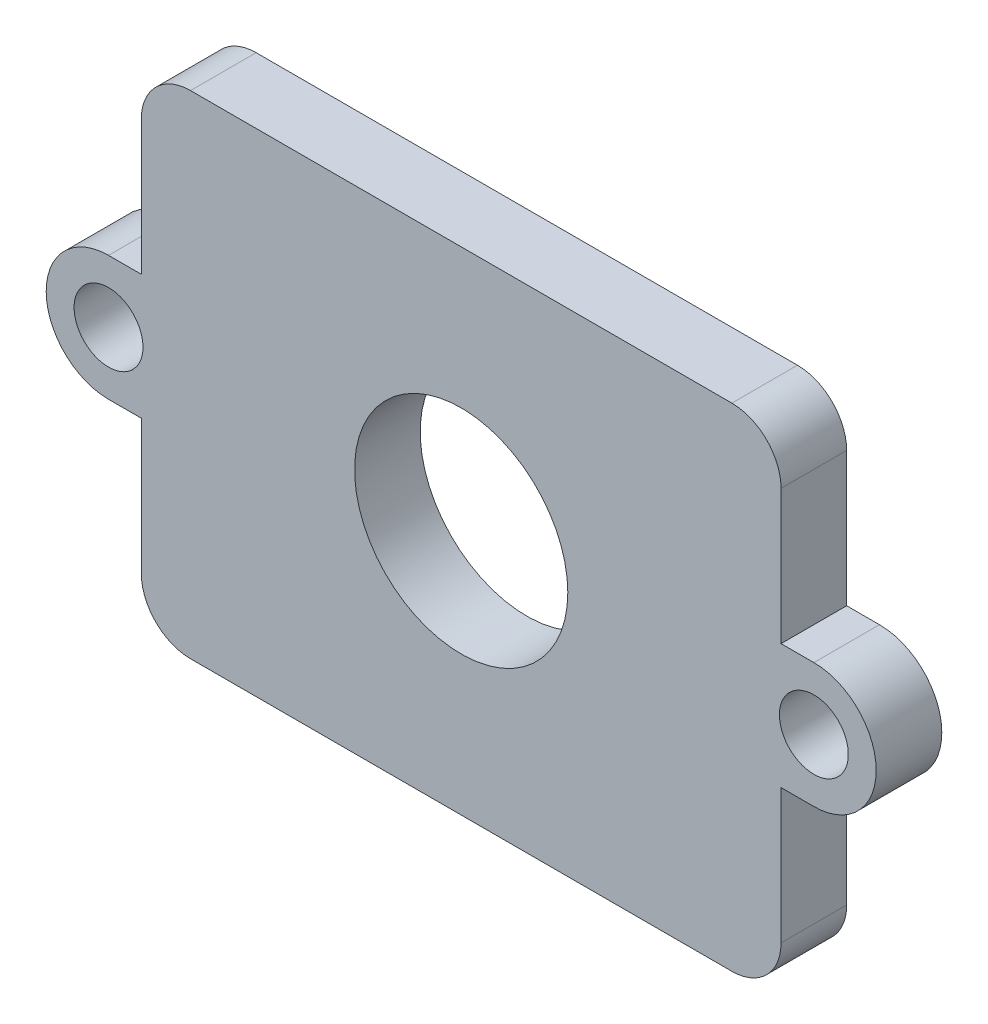
SolidWorks part; units mm, degrees
ref_plane "Front Plane" through (0, 0, 0) normal (0, 0, 1) x (1, 0, 0)
ref_plane "Top Plane" through (0, 0, 0) normal (0, 1, 0) x (1, 0, 0)
ref_plane "Right Plane" through (0, 0, 0) normal (1, 0, 0) x (0, 0, -1)
sketch "Sketch1" plane through (0, 0, 0) normal (0, 0, 1) x (1, 0, 0)
  line L0 (19.5, 3.8) -> (21.5, 3.8)
  line L1 (-19.5, 15) -> (19.5, 15)
  line L3 (-19.5, -15) -> (19.5, -15)
  line L4 (19.5, 15) -> (19.5, 3.8)
  line L5 (-19.5, 15) -> (19.5, -15) construction
  line L6 (-19.5, -15) -> (19.5, 15) construction
  line L7 (21.5, 3.8) -> (21.5, -3.8)
  line L8 (21.5, -3.8) -> (19.5, -3.8)
  line L9 (0, 15) -> (0, -15) construction
  line L10 (-21.5, -3.8) -> (-19.5, -3.8)
  line L11 (-21.5, 3.8) -> (-21.5, -3.8)
  line L12 (-19.5, 15) -> (-19.5, 3.8)
  line L13 (-19.5, 3.8) -> (-21.5, 3.8)
  line L14 (-19.5, -3.8) -> (-19.5, -15)
  line L15 (19.5, -3.8) -> (19.5, -15)
  circle A0 centre (0, 0) radius 6.5
  point P0 (0, 0)
  point P8 (21.5, 0)
  dimension "D3" = 13
  dimension "D1" = 7.6
  dimension "D2" = 30
  dimension "D4" = 39
  dimension "D5" = 43
extrude "Boss-Extrude1" add sketch "Sketch1" along normal blind 4
sketch "Sketch2" plane through (0, 0, 4) normal (0, 0, 1) x (1, 0, 0)
  line L0 (-21.5, 3.8) -> (-21.5, -3.8) construction
  line L1 (-21.5, -3.8) -> (-19.5, -3.8) construction
  line L2 (-21.5, 3.8) -> (-21.5, -3.8)
  arc A0 (-21.5, 3.8) -> (-21.5, -3.8) centre (-21.5, 0) ccw
extrude "Boss-Extrude2" add sketch "Sketch2" against normal up to surface (4 mm away) up to face at (0, 0, 0)
sketch "Sketch3" plane through (0, 0, 4) normal (0, 0, 1) x (1, 0, 0)
  circle A0 centre (-21.5, 0) radius 2.1
  arc A1 (-21.5, 3.8) -> (-21.5, -3.8) centre (-21.5, 0) ccw construction
  dimension "D1" = 4.2
extrude "Cut-Extrude1" cut sketch "Sketch3" against normal through all
ref_plane "Plane1" through (0, 0, 0) normal (-1, 0, 0) x (0, 0, 1)
mirror "Mirror1" about plane through (0, 0, 0) normal (-1, 0, 0) of "Boss-Extrude2", "Cut-Extrude1"
fillet "Fillet1" radius 3 4 edges at (19.5, -15, 2) (-19.5, -15, 2) (-19.5, 15, 2) (19.5, 15, 2)
